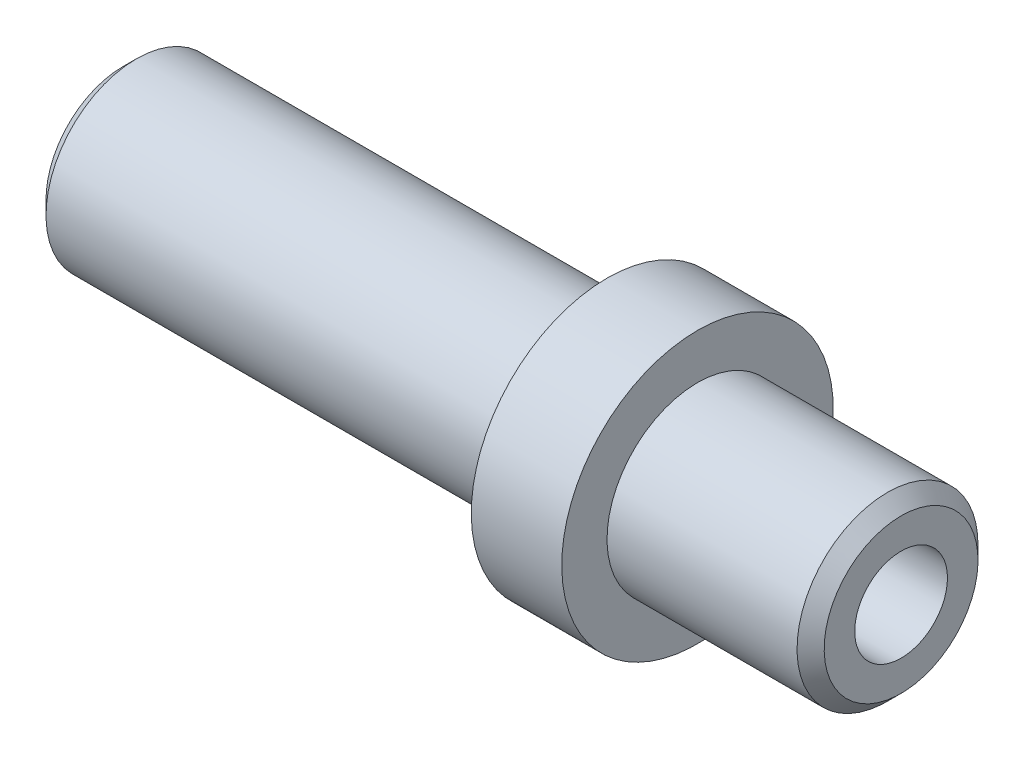
SolidWorks part; units mm, degrees
material "Acier allié inoxydable"
ref_plane "Face" through (0, 0, 0) normal (0, 0, 1) x (1, 0, 0)
ref_plane "Dessus" through (0, 0, 0) normal (0, 1, 0) x (1, 0, 0)
ref_plane "Droite" through (0, 0, 0) normal (1, 0, 0) x (0, 0, -1)
sketch "Esquisse1" plane through (0, 0, 0) normal (0, 0, 1) x (1, 0, 0)
  line L0 (0, 0) -> (0, 2)
  line L1 (0, 2) -> (10.7, 2)
  line L2 (10.7, 2) -> (10.7, 3)
  line L3 (10.7, 3) -> (12.7, 3)
  line L4 (12.7, 3) -> (12.7, 2)
  line L5 (12.7, 2) -> (17.2, 2)
  line L6 (17.2, 2) -> (17.2, 0)
  line L7 (17.2, 0) -> (0, 0) construction
  line L8 (0, 0) -> (17.2, 0)
  dimension "D1" = 4
  dimension "D2" = 10.7
  dimension "D3" = 6
  dimension "D4" = 2
  dimension "D5" = 4.5
  dimension "D6" = 4
revolve "Révolution1" add sketch "Esquisse1" angle 360 about L7
hole_wizard "Trou taraudé M2.51" positions "Esquisse6" profile "Esquisse5" tap size "M2.5" standard "Iso"
sketch "Esquisse6" plane through (0, 0, 0) normal (-1, 0, 0) x (0, 0, 1)
  point P0 (0, 0)
sketch "Esquisse5" plane through (0, 0, 0) normal (0, 1, 0) x (0, 0, 1)
  line L0 (0, 0) -> (0, 8.6159)
  line L1 (0, 8.6159) -> (1.025, 8)
  line L2 (1.025, 8) -> (1.025, 0)
  line L5 (1.025, 0) -> (0, 0)
  line L10 (0, 8.6159) -> (-1.025, 8) construction
  line L11 (0, -6.35) -> (0, 107.95) construction
  dimension "Diamètre du trou pour taraudage" = 2.05
  dimension "Profondeur du trou pour taraudage" = 8
  dimension "Angle de pointe" = 118
cosmetic thread "Filetage de perçage4" parameters "D1"=6, "D2"=2.5
hole_wizard "Trou taraudé M2.52" positions "Esquisse8" profile "Esquisse7" tap size "M2.5" standard "Iso"
sketch "Esquisse8" plane through (17.2, 0, 0) normal (1, 0, 0) x (0, 0, -1)
  point P0 (0, 0)
cosmetic thread "Filetage de perçage5" parameters "D1"=6, "D2"=2.5
sketch "Esquisse7" plane through (17.2, 0, 0) normal (0, 1, 0) x (0, 0, -1)
  line L0 (0, 0) -> (0, 8.6159)
  line L1 (0, 8.6159) -> (1.025, 8)
  line L2 (1.025, 8) -> (1.025, 0)
  line L5 (1.025, 0) -> (0, 0)
  line L10 (0, 8.6159) -> (-1.025, 8) construction
  line L11 (0, -6.35) -> (0, 107.95) construction
  dimension "Diamètre du trou pour taraudage" = 2.05
  dimension "Profondeur du trou pour taraudage" = 8
  dimension "Angle de pointe" = 118
chamfer "Chanfrein1" distance 0.3 angle 45 2 edges at (17.2, 2, 0) (0, 2, 0)
